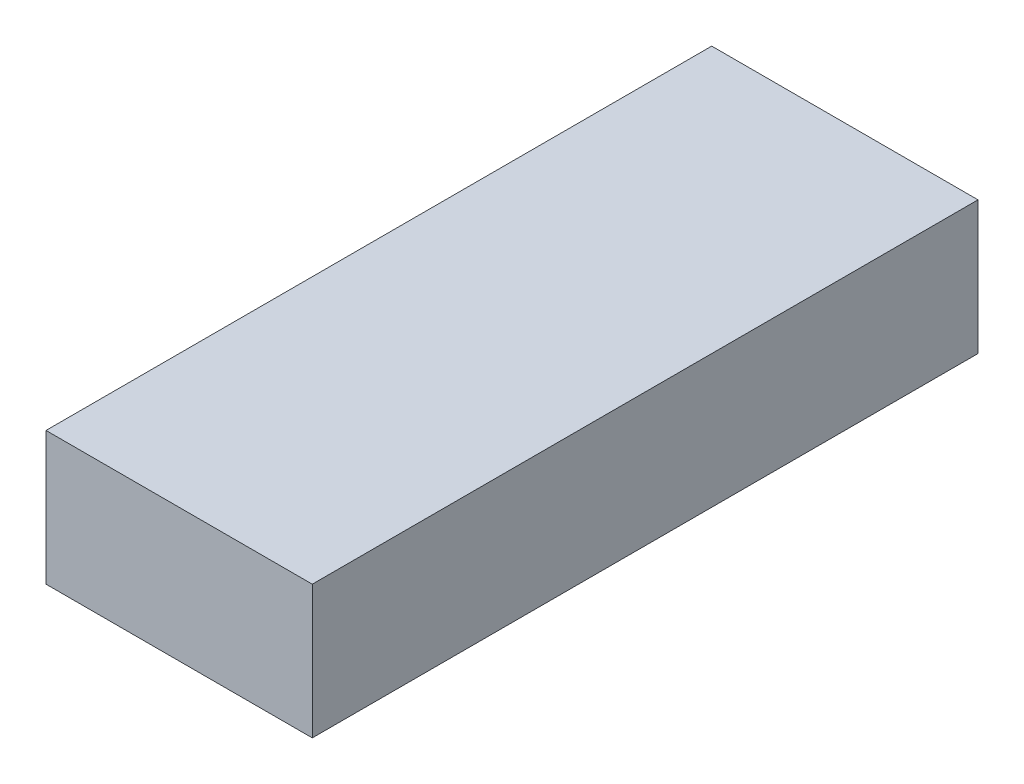
SolidWorks part; units mm, degrees
ref_plane "Front Plane" through (0, 0, 0) normal (0, 0, 1) x (1, 0, 0)
ref_plane "Top Plane" through (0, 0, 0) normal (0, 1, 0) x (1, 0, 0)
ref_plane "Right Plane" through (0, 0, 0) normal (1, 0, 0) x (0, 0, -1)
sketch "Sketch1" plane through (0, 0, 0) normal (0, 1, 0) x (1, 0, 0)
  line L0 (0, 0) -> (0, 63.5)
  line L1 (0, 63.5) -> (25.4, 63.5)
  line L2 (25.4, 63.5) -> (25.4, 0)
  line L3 (25.4, 0) -> (0, 0)
  dimension "D1" = 63.5
  dimension "D2" = 25.4
extrude "Boss-Extrude1" add sketch "Sketch1" along normal blind 12.7
